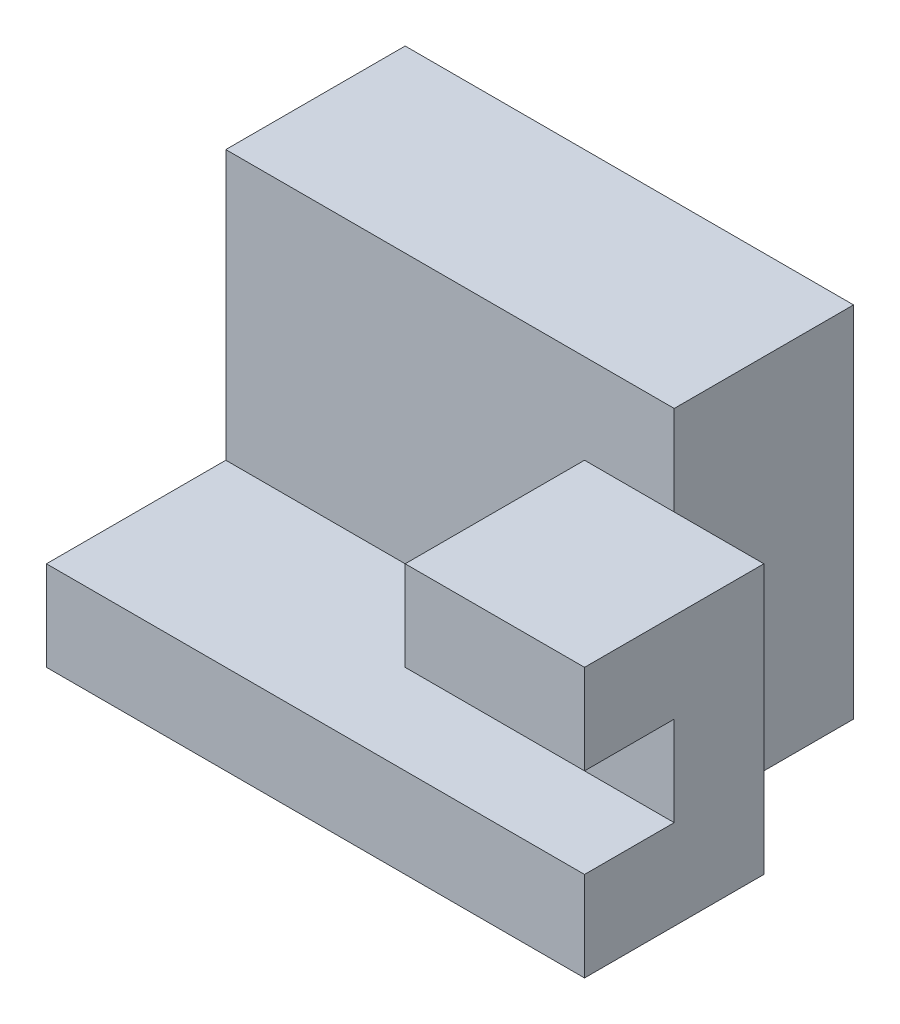
SolidWorks part; units mm, degrees
ref_plane "前基準面" through (0, 0, 0) normal (0, 0, 1) x (1, 0, 0)
ref_plane "上基準面" through (0, 0, 0) normal (0, 1, 0) x (1, 0, 0)
ref_plane "右基準面" through (0, 0, 0) normal (1, 0, 0) x (0, 0, -1)
sketch "草圖1" plane through (0, 0, 0) normal (1, 0, 0) x (0, 0, -1)
  line L1 (0, 0) -> (10, 0)
  line L2 (0, 0) -> (0, 20)
  line L3 (0, 20) -> (10, 20)
  line L4 (10, 0) -> (10, 20)
  line L5 (0, 0) -> (-10, 0)
  line L6 (0, 0) -> (0, 5)
  line L7 (0, 5) -> (-10, 5)
  line L8 (-10, 0) -> (-10, 5)
  dimension "D1" = 20
  dimension "D2" = 10
  dimension "D3" = 10
  dimension "D4" = 5
extrude "填料-伸長1" add sketch "草圖1" against normal blind 25 contours L8 L5 L2 L7 | L1 L4 L3 L2
sketch "草圖2" plane through (0, 0, 0) normal (1, 0, 0) x (0, 0, -1)
  line L0 (0, 5) -> (0, 20) construction
  line L1 (-10, 15) -> (0, 15)
  line L2 (-10, 15) -> (-10, 10)
  line L3 (-10, 0) -> (-10, 5) construction
  line L4 (0, 15) -> (0, 0)
  line L5 (10, 0) -> (-10, 0) construction
  line L6 (-10, 0) -> (-10, 5)
  line L7 (0, 0) -> (-10, 0)
  line L8 (-10, 10) -> (-5, 10)
  line L9 (-5, 10) -> (-5, 5)
  line L10 (0, 5) -> (-10, 5) construction
  line L11 (-5, 5) -> (-10, 5)
  point P6 (-5, 0)
  dimension "D1" = 5
  dimension "D2" = 15
  dimension "D3" = 10
  dimension "D4" = 5
extrude "填料-伸長2" add sketch "草圖2" along normal blind 5 and the other way blind 5
